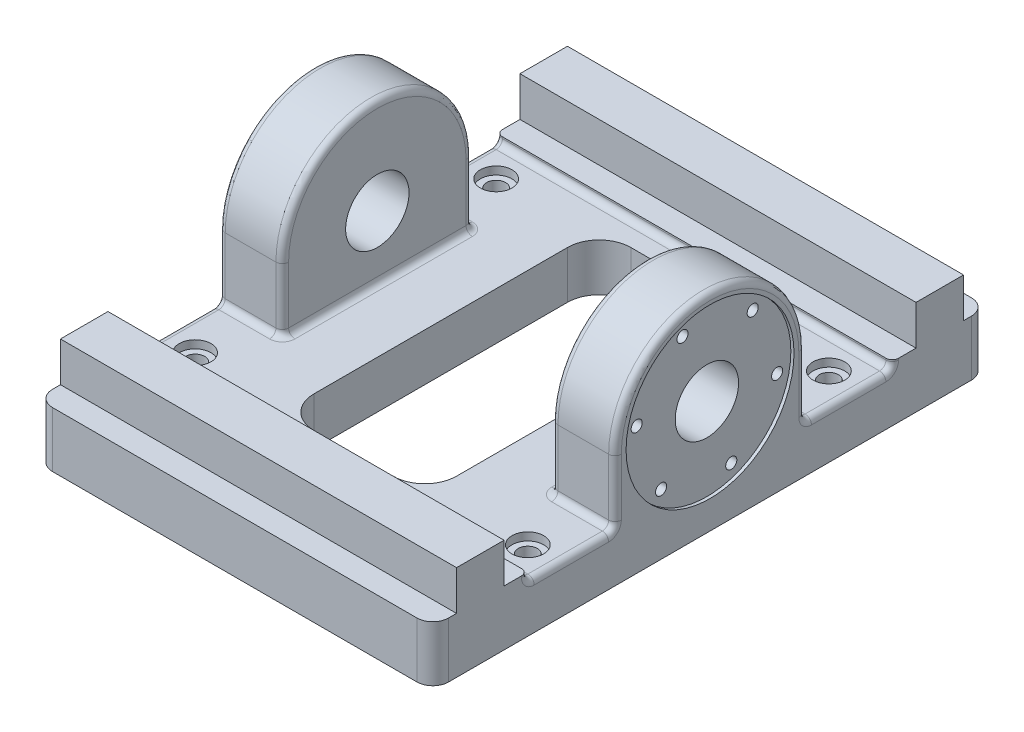
SolidWorks part; units mm, degrees
ref_plane "Front Plane" through (0, 0, 0) normal (0, 0, 1) x (1, 0, 0)
ref_plane "Top Plane" through (0, 0, 0) normal (0, 1, 0) x (1, 0, 0)
ref_plane "Right Plane" through (0, 0, 0) normal (1, 0, 0) x (0, 0, -1)
sketch "Sketch1" plane through (0, 0, 0) normal (0, 1, 0) x (1, 0, 0)
  line L1 (125, 175) -> (-125, 175)
  line L2 (125, 175) -> (125, -175)
  line L3 (125, -175) -> (-125, -175)
  line L4 (-125, 175) -> (-125, -175)
  line L5 (125, 175) -> (-125, -175) construction
  line L6 (125, -175) -> (-125, 175) construction
  point P0 (0, 0)
  dimension "D1" = 250
  dimension "D2" = 350
extrude "Boss-Extrude1" add sketch "Sketch1" along normal blind 30
sketch "Sketch2" plane through (0, 30, 0) normal (0, 1, 0) x (1, 0, 0)
  line L0 (-125, -175) -> (125, -175) construction
  line L1 (-125, -130) -> (125, -130)
  line L2 (-125, -130) -> (-125, -160)
  line L3 (-125, -160) -> (125, -160)
  line L4 (125, -130) -> (125, -160)
  line L5 (125, -175) -> (125, 175) construction
  line L6 (-125, 175) -> (-125, -175) construction
  dimension "D1" = 15
  dimension "D2" = 30
extrude "Boss-Extrude2" add sketch "Sketch2" along normal blind 30
sketch "Sketch3" plane through (0, 30, 0) normal (0, 1, 0) x (1, 0, 0)
  line L1 (125, -115) -> (-125, -115)
  line L2 (125, -115) -> (125, -175)
  line L3 (125, -175) -> (-125, -175)
  line L4 (-125, -115) -> (-125, -175)
  line L6 (-125, -175) -> (125, -175) construction
  line L7 (125, -175) -> (125, -160) construction
  line L8 (-125, -160) -> (-125, -175) construction
  dimension "D1" = 60
extrude "Boss-Extrude3" add sketch "Sketch3" along normal blind 5
mirror "Mirror1" about plane through (0, 0, 0) normal (0, 0, 1) of "Boss-Extrude3", "Boss-Extrude2"
sketch "Sketch4" plane through (-125, 0, 0) normal (-1, 0, 0) x (0, 0, 1)
  line L0 (60, 30) -> (-60, 30)
  line L1 (-115, 30) -> (115, 30) construction
  line L2 (-60, 30) -> (-60, 70)
  line L3 (60, 70) -> (60, 30)
  line L5 (-175, 0) -> (175, 0) construction
  arc A0 (-60, 70) -> (60, 70) centre (0, 70) cw
  point P10 (0, 0)
  dimension "D2" = 10
  dimension "D1" = 40
extrude "Boss-Extrude4" add sketch "Sketch4" against normal blind 40
sketch "Sketch5" plane through (-125, 0, 0) normal (-1, 0, 0) x (0, 0, 1)
  circle A0 centre (0, 70.7783) radius 53
  dimension "D1" = 106
extrude "Cut-Extrude1" cut sketch "Sketch5" against normal blind 2
sketch "Sketch6" plane through (-125, 0, 0) normal (-1, 0, 0) x (0, 0, 1)
  line L0 (0, 70.7783) -> (45, 70.7783) construction
  line L1 (0, 70.7783) -> (15.3909, 113.0645) construction
  circle A0 centre (0, 70.7783) radius 45 construction
  circle A1 centre (0, 70.7783) radius 53 construction
  circle A2 centre (15.3909, 113.0645) radius 3.5
  dimension "D1" = 90
  dimension "D3" = 7
  dimension "D2" = 70
extrude "Cut-Extrude2" cut sketch "Sketch6" against normal blind 30
pattern_circular "CirPattern1" count 6 over 360 about axis through (0, 70.7783, 0) along (1, 0, 0) of "Cut-Extrude2"
mirror "Mirror2" about plane through (0, 0, 0) normal (1, 0, 0) of "CirPattern1", "Cut-Extrude2", "Cut-Extrude1", "Boss-Extrude4"
sketch "Sketch7" plane through (0, 0, 0) normal (1, 0, 0) x (0, 0, -1)
  circle A0 centre (0, 70) radius 20
  arc A1 (60, 70) -> (-60, 70) centre (0, 70) ccw construction
  dimension "D1" = 40
extrude "Cut-Extrude3" cut sketch "Sketch7" against normal through all both and the other way through all
sketch "Sketch8" plane through (0, 30, 0) normal (0, 1, 0) x (1, 0, 0)
  line L1 (-25, 100) -> (25, 100)
  line L2 (-45, 80) -> (-45, -80)
  line L3 (-25, -100) -> (25, -100)
  line L4 (45, 80) -> (45, -80)
  line L5 (-45, 100) -> (45, -100) construction
  line L6 (-45, -100) -> (45, 100) construction
  arc A0 (-45, -80) -> (-25, -100) centre (-25, -80) ccw
  arc A1 (25, -100) -> (45, -80) centre (25, -80) ccw
  arc A2 (25, 100) -> (45, 80) centre (25, 80) cw
  arc A3 (-25, 100) -> (-45, 80) centre (-25, 80) ccw
  point P0 (0, 0)
  dimension "D3" = 20
  dimension "D1" = 90
  dimension "D2" = 200
extrude "Cut-Extrude4" cut sketch "Sketch8" against normal up to next
sketch "Sketch9" plane through (0, 30, 0) normal (0, 1, 0) x (1, 0, 0)
  line L0 (-125, 175) -> (125, 175) construction
  line L1 (125, 60) -> (125, 115) construction
  point P0 (105, 95)
  dimension "D1" = 80
  dimension "D2" = 20
hole_wizard "Hole1" positions "Sketch11" profile "Sketch12" legacy
sketch "Sketch11" plane through (0, 30, 0) normal (0, 1, 0) x (-1, 0, 0)
  point P0 (-105, -95)
sketch "Sketch12" plane through (105, 30, -95) normal (1, 0, 0) x (0, 0, 1)
  line L0 (0, 0) -> (0, 30)
  line L1 (0, 30) -> (6, 30)
  line L2 (6, 30) -> (6, 5)
  line L3 (6, 5) -> (10, 5)
  line L4 (10, 5) -> (10, 0)
  line L5 (10, 0) -> (0, 0)
  line L6 (0, 110) -> (0, -10) construction
  dimension "Diameter" = 12
  dimension "Depth" = 30
  dimension "C-Bore Diameter" = 20
  dimension "C-Bore Depth" = 5
pattern_linear "LPattern1" count 2 spacing 190 along (0, 0, 1) count 2 spacing 210 along (-1, 0, 0) of "Hole1"
fillet "Fillet1" radius 10 4 edges at (-125, 17.5, -175) (125, 17.5, -175) (-125, 17.5, 175) (125, 17.5, 175)
fillet "Fillet2" radius 4 28 edges at (125, 32.5, -115) (-125, 32.5, -115) (125, 30, -87.5) (-125, 30, -87.5) (105, 30, -60) (125, 32.5, 115) (-125, 32.5, 115) (-105, 30, -60) (85, 30, 0) (125, 30, 87.5) (-125, 30, 87.5) (-85, 30, 0) (85, 50, 60) (85, 50, -60) (125, 50, 60) (125, 50, -60) (-125, 50, 60) (-85, 50, 60) (-125, 50, -60) (-85, 50, -60) (0, 30, 115) (0, 30, -115) (-105, 30, 60) (105, 30, 60) (85, 130, 0) (125, 130, 0) (-125, 130, 0) (-85, 130, 0)
